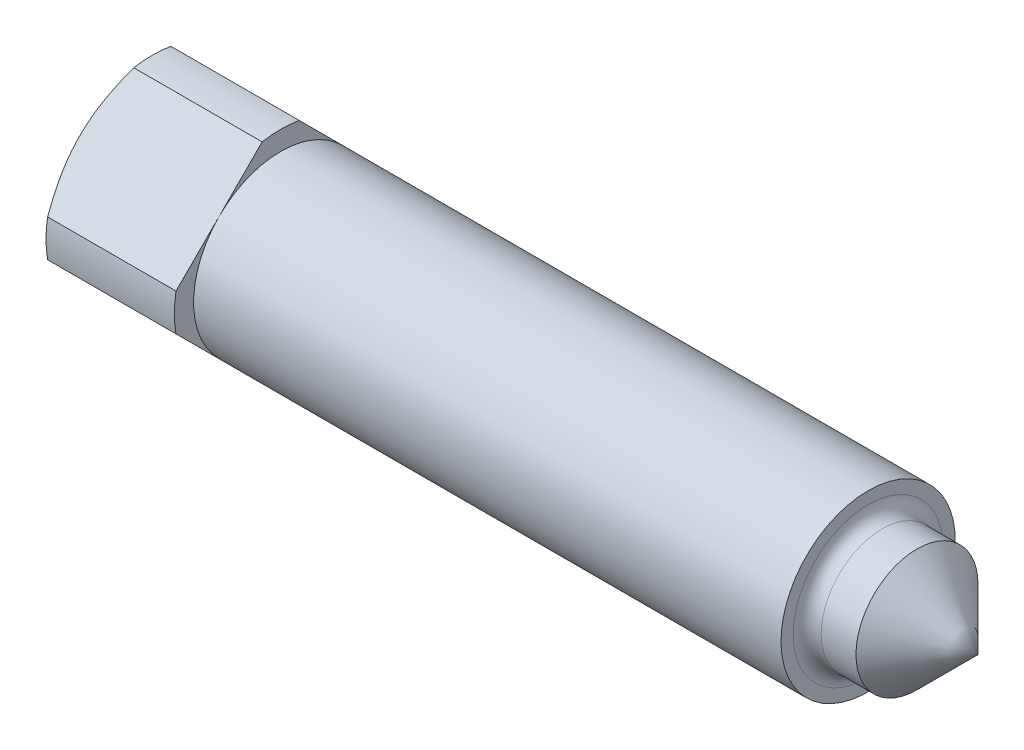
SolidWorks part; units mm, degrees
ref_plane "Front" through (0, 0, 0) normal (0, 0, 1) x (1, 0, 0)
ref_plane "Top" through (0, 0, 0) normal (0, 1, 0) x (1, 0, 0)
ref_plane "Right" through (0, 0, 0) normal (1, 0, 0) x (0, 0, -1)
other "Configuration Table"
sketch "Sketch1" plane through (0, 0, 0) normal (1, 0, 0) x (0, 0, -1)
  circle A0 centre (0, 0) radius 6.1
  dimension "e" = 12.2
extrude "BaseHead" add sketch "Sketch1" along normal blind 8
sketch "Sketch2" plane through (0, 2.6629, -1.4921) normal (-1, 0, 0) x (0, 0, 1)
  line L1 (8.5632, -2.6629) -> (1.4921, 4.4081)
  line L2 (1.4921, 4.4081) -> (-5.579, -2.6629)
  line L3 (-5.579, -2.6629) -> (1.4921, -9.734)
  line L4 (1.4921, -9.734) -> (8.5632, -2.6629)
  circle A0 centre (1.4921, -2.6629) radius 5 construction
  dimension "s" = 10
extrude "Cut-Extrude1" cut sketch "Sketch2" against normal blind 8 flip side to cut
sketch "Sketch3" plane through (1.2597, -5.2747, 0) normal (0, 0, 1) x (0, -1, 0)
  line L0 (-11.9847, -1.2597) -> (-10.2747, -1.2597)
  line L2 (-10.2747, -1.2597) -> (-11.9847, -0.2724)
  line L3 (-11.9847, -0.2724) -> (-11.9847, -1.2597)
  line L4 (-5.2747, 0.2856) -> (-5.2747, -6.82) construction
  line L6 (-6.3394, -1.2597) -> (-11.2811, -1.2597) construction
  dimension "d2" = 10
  dimension "D3" = 30
  dimension "D1" = 13.42
revolve "Cut-Revolve1" cut sketch "Sketch3" angle 360 about L4
sketch "Sketch4" plane through (-10.3472, 12.8472, 0) normal (0, 0, 1) x (0, -1, 0)
  line L0 (12.8472, 18.3472) -> (17.8472, 18.3472)
  line L1 (12.8472, 58.3472) -> (16.3472, 54.8472)
  line L2 (17.8472, 18.3472) -> (17.8472, 52.0472)
  line L3 (11.7825, 18.3472) -> (6.8409, 18.3472) construction
  line L4 (16.3472, 52.0472) -> (16.3472, 54.8472)
  line L5 (12.8472, 58.3472) -> (12.8472, 18.3472)
  line L6 (12.8472, 24.434) -> (12.8472, -1.2396) construction
  line L8 (17.8472, 52.0472) -> (16.3472, 52.0472)
  dimension "d" = 10
  dimension "l" = 40
  dimension "dp" = 7
  dimension "z" = 6.3
  dimension "D2" = 45
revolve "BaseBody" add sketch "Sketch4" angle 360 about L6
cosmetic thread "ThreadCosmetic1" [suppressed] parameters "D1"=27.7, "d"=8.376
fillet "Fillet1" radius 0.8 1 edges at (41.7, 3.5, 0)
fillet "HeadFillet" [suppressed] radius 0.4
sketch "Sketch5" plane through (0, 0, 0) normal (0, 0, 1) x (1, 0, 0)
  line L0 (41.7, 4.2968) -> (42.106, 5)
  line L1 (42.106, 5) -> (42.106, 5.812)
  line L2 (42.106, 5.812) -> (41.294, 5.812)
  line L3 (41.294, 5.812) -> (41.294, 5)
  line L4 (41.294, 5) -> (41.7, 4.2968)
  line L5 (0, 0) -> (22.7829, 0) construction
  line L6 (0, 3.5355) -> (0, -3.5355) construction
  line L7 (41.7, -5) -> (41.7, 5) construction
  dimension "D1" = 10
  dimension "D2" = 0.812
revolve "Cut-Revolve10" [suppressed] cut sketch "Sketch5" angle 360 about L5
pattern_linear "LPattern10" [suppressed] count 28 spacing 0.9744 along (1, 0, 0)
equation "\"D1@Fillet1\" = 2 * \"r@HeadFillet\""
equation "\"d2@Sketch3\" = \"s@Sketch2\""
equation "\"D1@Sketch3\" = \"e@Sketch1\" * 1.1"
equation "\"k+c@BaseHead\" = \"k@Cut-Extrude1\""
equation "\"D1@Sketch5\" = \"d@Sketch4\""
equation "\"D2@Sketch5\" =  ( \"d@Sketch4\" - \"d@ThreadCosmetic1\" )  / 2"
equation "\"D3@LPattern10\" = \"D2@Sketch5\" * 1.2"
equation "\"D1@LPattern10\" = \"D1@ThreadCosmetic1\" / \"D3@LPattern10\""
